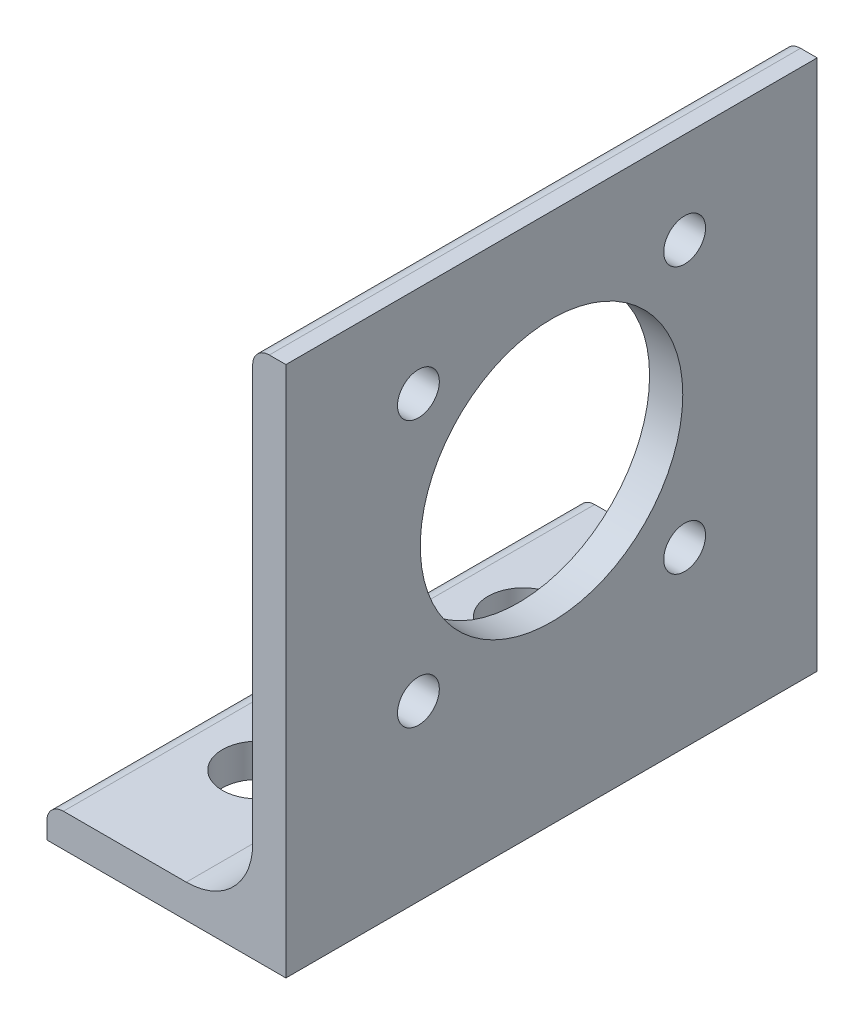
SolidWorks part; units mm, degrees
ref_plane "Front Plane" through (0, 0, 0) normal (0, 0, 1) x (1, 0, 0)
ref_plane "Top Plane" through (0, 0, 0) normal (0, 1, 0) x (1, 0, 0)
ref_plane "Right Plane" through (0, 0, 0) normal (1, 0, 0) x (0, 0, -1)
sketch "Sketch2" plane through (0, 0, 0) normal (0, 0, 1) x (1, 0, 0)
  line L0 (-25.4, 0) -> (25.4, 0)
  line L1 (25.4, 0) -> (25.4, 50.8)
  line L2 (25.4, 50.8) -> (22.225, 50.8) construction
  line L3 (22.225, 49.2125) -> (22.225, 9.525)
  line L4 (15.875, 3.175) -> (-23.8125, 3.175)
  line L5 (-25.4, 0) -> (-25.4, 3.175) construction
  line L6 (23.8125, 50.8) -> (25.4, 50.8)
  line L7 (-25.4, 1.5875) -> (-25.4, 0)
  arc A0 (22.225, 49.2125) -> (23.8125, 50.8) centre (23.8125, 49.2125) cw
  arc A1 (-25.4, 1.5875) -> (-23.8125, 3.175) centre (-23.8125, 1.5875) cw
  arc A2 (22.225, 9.525) -> (15.875, 3.175) centre (15.875, 9.525) cw
  dimension "Inside Radius" = 6.35
  dimension "Vert" = 50.8
  dimension "Horz" = 50.8
  dimension "Thickness" = 3.175
extrude "Boss-Extrude1" add sketch "Sketch2" along normal mid plane 50.8
sketch "Break Locations" plane through (0, 0, 0) normal (1, 0, 0) x (0, 0, -1)
  line L1 (-25.4, 0) -> (-25.4, 50.8) construction
  line L2 (25.4, 0) -> (25.4, 50.8) construction
  point P0 (17.78, 0)
  point P1 (-17.78, 0)
  dimension "D1" = 43.18
  dimension "D2" = 43.18
ref_plane "Contact Plane 1" through (0, 3.175, 0) normal (0, 1, 0) x (1, 0, 0)
ref_plane "Contact Plane 2" through (22.225, 0, 0) normal (-1, 0, 0) x (0, 0, 1)
sketch "Sketch3" plane through (0, 0, -25.4) normal (0, 0, -1) x (-1, 0, 0)
  line L0 (25.4, 1.5875) -> (25.4, 0) construction
  line L1 (-2.54, 8.3996) -> (25.4, 8.3996)
  line L2 (-2.54, 8.3996) -> (-2.54, -5.4313)
  line L3 (-2.54, -5.4313) -> (25.4, -5.4313)
  line L4 (25.4, 8.3996) -> (25.4, -5.4313)
  line L5 (-25.4, 0) -> (-25.4, 50.8) construction
  point P6 (25.4, 0.7937)
  dimension "D1" = 22.86
extrude "Cut-Extrude1" cut sketch "Sketch3" against normal through all
fillet "Fillet1" radius 1.5875 1 edges at (2.54, 3.175, 0)
sketch "Sketch4" plane through (0, 3.175, 0) normal (0, 1, 0) x (1, 0, 0)
  line L0 (10.0013, 25.4) -> (10.0013, -25.4) construction
  line L1 (15.875, 25.4) -> (4.1275, 25.4) construction
  line L2 (15.875, -25.4) -> (4.1275, -25.4) construction
  circle A0 centre (10.0013, 12.7) radius 3.3782
  circle A1 centre (10.0013, -12.7) radius 3.3782
  dimension "D1" = 6.7564
  dimension "D2" = 25.4
  dimension "D3" = 12.7
extrude "Cut-Extrude2" cut sketch "Sketch4" against normal through all
sketch "Sketch5" plane through (25.4, 0, 0) normal (1, 0, 0) x (0, 0, -1)
  line L0 (-25.4, 0) -> (25.4, 0) construction
  line L1 (25.4, 0) -> (25.4, 50.8) construction
  line L2 (0, 50.8) -> (0, 0) construction
  line L3 (-25.4, 50.8) -> (25.4, 50.8) construction
  line L4 (-25.4, 25.4) -> (25.4, 25.4) construction
  line L5 (-25.4, 0) -> (-25.4, 50.8) construction
  line L6 (0, 29.3279) -> (12.7279, 42.0558) construction
  line L7 (0, 29.3279) -> (12.7279, 16.6) construction
  circle A0 centre (12.7279, 16.6) radius 2
  circle A1 centre (-12.7279, 16.6) radius 2
  circle A2 centre (-12.7279, 42.0558) radius 2
  circle A3 centre (12.7279, 42.0558) radius 2
  circle A4 centre (0, 29.3279) radius 18 construction
  circle A5 centre (0, 29.3279) radius 12.55
  dimension "D1" = 4
  dimension "D3" = 36
  dimension "D6" = 25.1
  dimension "D2" = 45
  dimension "D4" = 45
  dimension "D5" = 16.6
extrude "Cut-Extrude3" cut sketch "Sketch5" against normal through all
equation "\"D1@Break Locations\"=.85*\"Vert@Sketch2\""
equation "\"D2@Break Locations\"=\"D1@Break Locations\""
